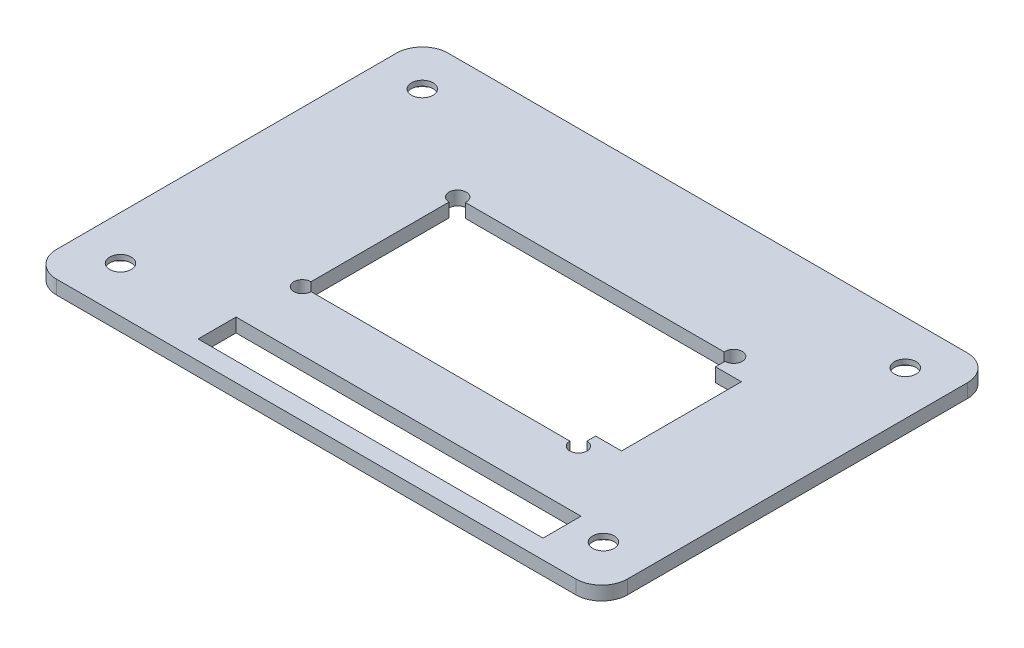
SolidWorks part; units mm, degrees
ref_plane "前视基准面" through (0, 0, 0) normal (0, 0, 1) x (1, 0, 0)
ref_plane "上视基准面" through (0, 0, 0) normal (0, 1, 0) x (1, 0, 0)
ref_plane "右视基准面" through (0, 0, 0) normal (1, 0, 0) x (0, 0, -1)
sketch "草图1" plane through (0, 0, 0) normal (0, 1, 0) x (1, 0, 0)
  line L1 (-30.1, -22.7) -> (30.1, -22.7)
  line L2 (-33.1, -19.7) -> (-33.1, 19.7)
  line L3 (-30.1, 22.7) -> (30.1, 22.7)
  line L4 (33.1, -19.7) -> (33.1, 19.7)
  line L5 (-33.1, -22.7) -> (33.1, 22.7) construction
  line L6 (-33.1, 22.7) -> (33.1, -22.7) construction
  arc A0 (30.1, 22.7) -> (33.1, 19.7) centre (30.1, 19.7) cw
  arc A1 (-33.1, 19.7) -> (-30.1, 22.7) centre (-30.1, 19.7) cw
  arc A2 (30.1, -22.7) -> (33.1, -19.7) centre (30.1, -19.7) ccw
  arc A3 (-30.1, -22.7) -> (-33.1, -19.7) centre (-30.1, -19.7) cw
  point P0 (0, 0)
  dimension "D3" = 3
  dimension "D4" = 3
  dimension "D1" = 45.4
  dimension "D2" = 66.2
extrude "凸台-拉伸1" add sketch "草图1" along normal blind 1.6
sketch "草图5" plane through (0, 0, 0) normal (0, -1, 0) x (1, 0, 0)
  line L0 (-33.1, -19.7) -> (-33.1, 19.7) construction
  line L1 (30.1, -22.7) -> (-30.1, -22.7) construction
  circle A0 centre (-28, -17.6) radius 2.6
  circle A1 centre (28, -17.6) radius 2.6
  circle A2 centre (28, 17.4) radius 2.6
  circle A3 centre (-28, 17.4) radius 2.6
  point P0 (-28, -17.6)
  point P10 (28, -17.6)
  point P13 (28, 17.4)
  point P16 (-28, 17.4)
  dimension "D3" = 5.2
  dimension "D1" = 5.1
  dimension "D2" = 5.1
  dimension "D4" = 2
  dimension "D5" = 2
extrude "正螺丝孔" cut sketch "草图5" against normal blind 1
sketch "草图7" plane through (0, 1, 0) normal (0, -1, 0) x (1, 0, 0)
  circle A0 centre (-28, -17.6) radius 1.25
  circle A1 centre (28, -17.6) radius 1.25
  circle A2 centre (28, 17.4) radius 1.25
  circle A3 centre (-28, 17.4) radius 1.25
  dimension "D1" = 2.5
  dimension "D2" = 2
  dimension "D3" = 2
extrude "背螺丝孔" cut sketch "草图7" against normal up to next
sketch "草图9" plane through (0, 0, 0) normal (0, -1, 0) x (-1, 0, 0)
  line L0 (-30.1, 22.7) -> (30.1, 22.7) construction
  line L5 (33.1, 19.7) -> (33.1, -19.7) construction
  line L6 (30.1, -22.7) -> (-30.1, -22.7) construction
  line L11 (15.9, -20.5) -> (-24.1, -20.5)
  line L12 (15.9, -20.5) -> (15.9, -16.1)
  line L13 (15.9, -16.1) -> (-24.1, -16.1)
  line L14 (-24.1, -20.5) -> (-24.1, -16.1)
  line L15 (-33.1, -19.7) -> (-33.1, 19.7) construction
  line L17 (-15.905, 1008.8) -> (-15.905, 8.7) construction
  line L18 (-16.9, -7.2) -> (-16.9, -8.2)
  line L19 (-15.905, 8.7) -> (14.105, 8.7)
  line L20 (-16.9, 7.8) -> (-16.9, 6.7)
  line L21 (-15.905, -9.2) -> (14.1, -9.2)
  line L22 (15.1, 7.8) -> (15.1, -8.2)
  line L23 (-16.9, -7.2) -> (-19.9, -7.2)
  line L25 (-16.9, 6.7) -> (-19.9, 6.7)
  line L26 (-19.9, -7.2) -> (-19.9, 6.7)
  line L27 (-15.905, -9.2) -> (-15.905, -1010.2) construction
  arc A0 (14.1, -9.2) -> (15.1, -8.2) centre (15.1, -9.2) ccw
  arc A1 (-16.9, -8.2) -> (-15.905, -9.2) centre (-16.905, -9.2) ccw
  arc A2 (15.1, 7.8) -> (14.105, 8.7) centre (15.1, 8.8) ccw
  arc A3 (-15.905, 8.7) -> (-16.9, 7.8) centre (-16.9, 8.8) ccw
  dimension "D8" = 2
  dimension "D6" = 2
  dimension "D2" = 32
  dimension "D3" = 18
  dimension "D4" = 14
  dimension "D5" = 18
  dimension "D7" = 3
  dimension "D9" = 40
  dimension "D10" = 4.4
  dimension "D11" = 2.2
  dimension "D12" = 9
  dimension "D13" = 2
extrude "切除-拉伸1" cut sketch "草图9" against normal up to next
